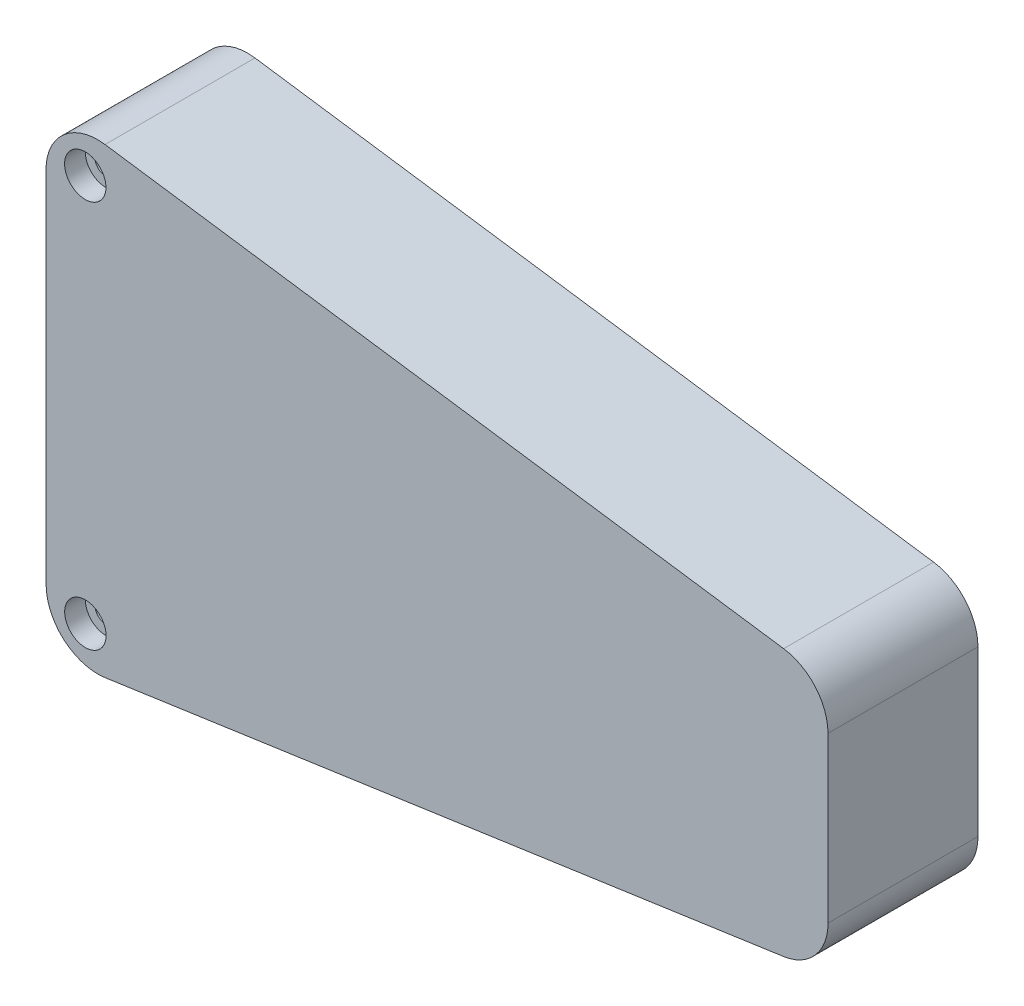
SolidWorks part; units mm, degrees
material "ABS"
ref_plane "Front Plane" through (0, 0, 0) normal (0, 0, 1) x (1, 0, 0)
ref_plane "Top Plane" through (0, 0, 0) normal (0, 1, 0) x (1, 0, 0)
ref_plane "Right Plane" through (0, 0, 0) normal (1, 0, 0) x (0, 0, -1)
sketch "Sketch2" plane through (0, 0, 0) normal (0, 0, 1) x (1, 0, 0)
  line L0 (244.7248, 219.4225) -> (244.6983, 300.4563)
  line L1 (244.6983, 300.4563) -> (385.9416, 280.2038)
  line L2 (385.9416, 280.2038) -> (385.9548, 239.7673)
  line L3 (385.9548, 239.7673) -> (244.7248, 219.4225)
extrude "Extrude-Thin1" add sketch "Sketch2" along normal blind 25 thin contours L1 L2 L3 L0 thin type one direction wall 5
sketch "Sketch3" plane through (0, 0, 0) normal (0, 0, 1) x (1, 0, 0)
  line L0 (239.7115, 259.9378) -> (390.9482, 259.9872) construction
  line L1 (239.7266, 213.6509) -> (239.6964, 306.2247) construction
  line L2 (390.9402, 284.5382) -> (390.9562, 235.4362) construction
  line L3 (244.6983, 300.4563) -> (256.0348, 298.8308)
  line L4 (244.6983, 300.4563) -> (385.9416, 280.2038) construction
  line L5 (256.0348, 298.8308) -> (244.702, 289.0039)
  line L6 (244.7248, 219.4225) -> (244.6983, 300.4563) construction
  line L7 (244.702, 289.0039) -> (244.6983, 300.4563)
  line L8 (244.721, 230.875) -> (244.7248, 219.4225)
  line L9 (256.0602, 221.0555) -> (244.721, 230.875)
  line L10 (244.7248, 219.4225) -> (256.0602, 221.0555)
  dimension "D1" = 15
extrude "Boss-Extrude1" add sketch "Sketch3" along normal up to surface (25 mm away) up to face at (315.3299, 259.9625, 25)
sketch "Sketch4" plane through (0, 0, 25) normal (0, 0, 1) x (1, 0, 0)
  line L0 (239.6964, 306.2247) -> (390.9402, 284.5382)
  line L1 (390.9402, 284.5382) -> (390.9562, 235.4362)
  line L2 (390.9562, 235.4362) -> (239.7266, 213.6509)
  line L3 (239.7266, 213.6509) -> (239.6964, 306.2247)
extrude "Boss-Extrude2" add sketch "Sketch4" along normal blind 4
fillet "Fillet1" radius 10 4 edges at (390.9402, 284.5382, 14.5) (390.9562, 235.4362, 14.5) (239.7266, 213.6509, 14.5) (239.6964, 306.2247, 14.5)
sketch "Sketch5" plane through (0, 0, 29) normal (0, 0, 1) x (1, 0, 0)
  line L0 (239.7115, 259.9378) -> (390.9482, 259.9872) construction
  line L1 (239.7002, 294.6847) -> (239.7229, 225.1909) construction
  line L2 (390.9534, 244.1017) -> (390.943, 275.8727) construction
  point P6 (247.2901, 297.4581)
  point P7 (247.3146, 222.4224)
hole_wizard "CBORE for M4 SHCS1" positions "3DSketch1" profile "Sketch6" counterbore size "M4" standard "ANSI Metric" end condition through all
sketch3d "3DSketch1"
  point P0 (247.2901, 297.4581, 29)
  point P3 (247.3146, 222.4224, 29)
sketch "Sketch6" plane through (247.2901, 297.4581, 29) normal (1, 0, 0) x (0, -1, 0)
  line L0 (0, 0) -> (0, 29)
  line L1 (0, 29) -> (2.15, 29)
  line L3 (2.15, 29) -> (2.15, 4)
  line L4 (2.15, 4) -> (4, 4)
  line L5 (4, 4) -> (4, 0)
  line L7 (4, 0) -> (0, 0)
  line L11 (0, -6.35) -> (0, 107.95) construction
  dimension "Thru Hole Dia." = 4.3
  dimension "Thru Hole Depth" = 29
  dimension "C'Bore Dia." = 8
  dimension "C'Bore Depth" = 4
fillet "Fillet2" radius 5 6 edges at (385.9416, 280.2038, 12.5) (385.9548, 239.7673, 12.5) (244.721, 230.875, 12.5) (256.0602, 221.0555, 12.5) (244.702, 289.0039, 12.5) (256.0348, 298.8308, 12.5)
